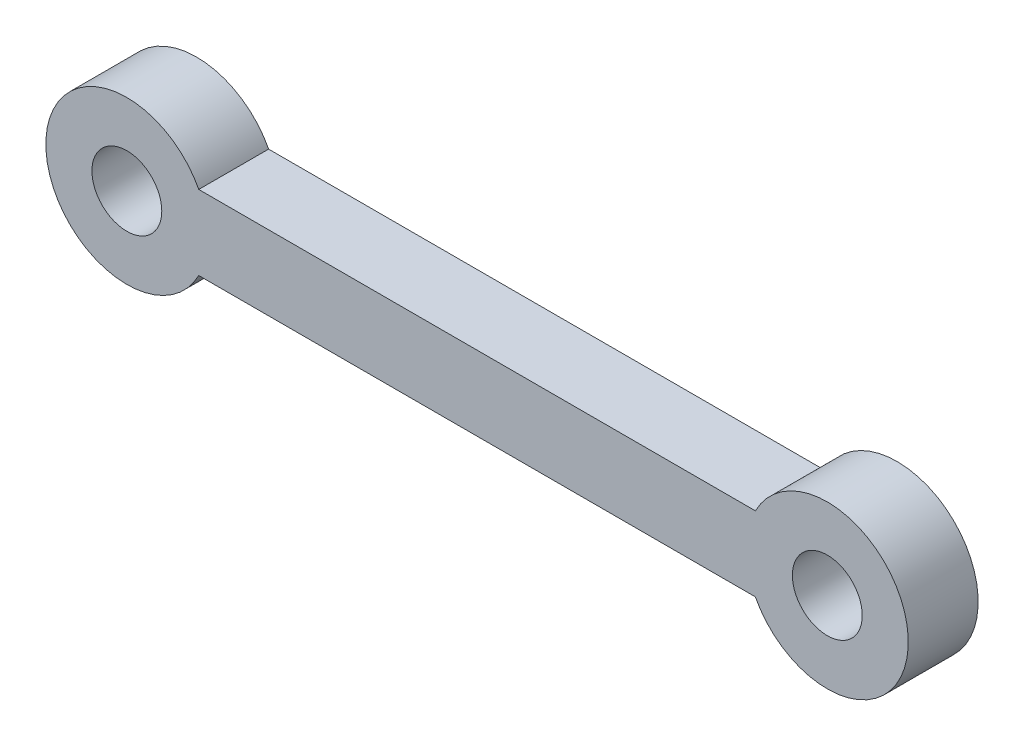
SolidWorks part; units mm, degrees
ref_plane "Front Plane" through (0, 0, 0) normal (0, 0, 1) x (1, 0, 0)
ref_plane "Top Plane" through (0, 0, 0) normal (0, 1, 0) x (1, 0, 0)
ref_plane "Right Plane" through (0, 0, 0) normal (1, 0, 0) x (0, 0, -1)
sketch "Sketch1" plane through (0, 0, 0) normal (0, 0, 1) x (1, 0, 0)
  line L1 (3.0874, 1.6) -> (26.9874, 1.6)
  line L2 (3.0874, -1.6) -> (26.9874, -1.6)
  line L3 (55, 0) -> (-55, 0) construction
  arc A0 (3.0874, 1.6) -> (3.0874, -1.6) centre (0, 0) ccw
  arc A2 (26.9874, 1.6) -> (26.9874, -1.6) centre (30.0748, 0) cw
  circle A3 centre (0, 0) radius 1.5
  circle A4 centre (30.0748, 0) radius 1.5
  point P12 (15.0374, -1.6)
  point P13 (15.0374, 1.6)
  dimension "D1" = 11.95
  dimension "D2" = 3.2
  dimension "D3" = 1.6
extrude "Boss-Extrude1" add sketch "Sketch1" along normal blind 3
